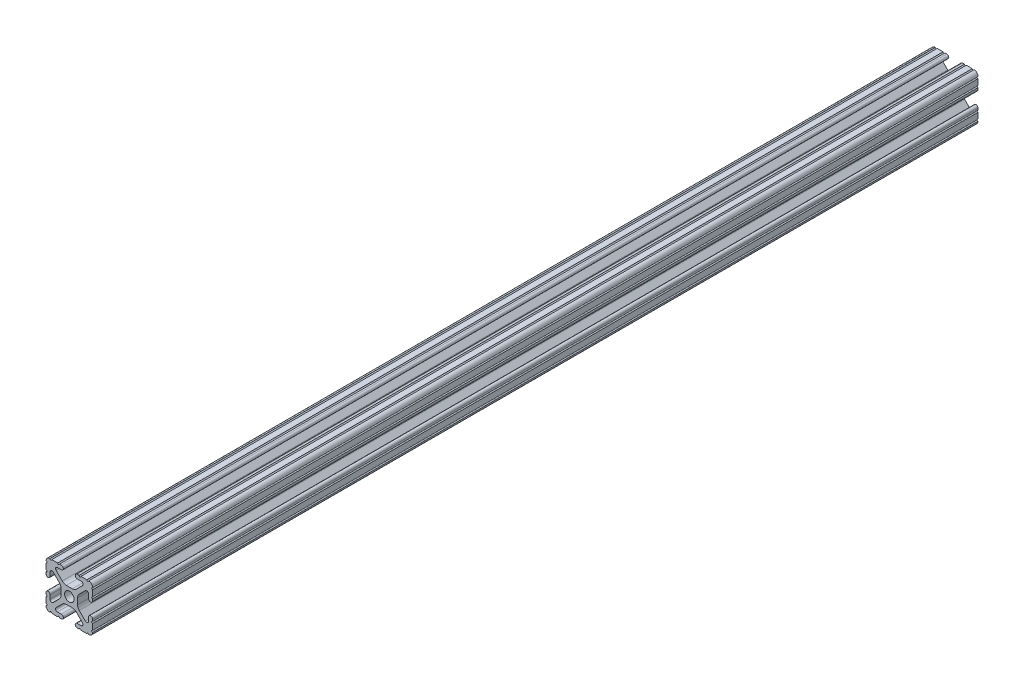
SolidWorks part; units mm, degrees
material "6061 Alloy"
ref_plane "Front Plane" through (0, 0, 0) normal (0, 0, 1) x (1, 0, 0)
ref_plane "Top Plane" through (0, 0, 0) normal (0, 1, 0) x (1, 0, 0)
ref_plane "Right Plane" through (0, 0, 0) normal (1, 0, 0) x (0, 0, -1)
ref_plane "Plane1" through (0, 0, -25.4) normal (0, 0, -1) x (-1, 0, 0)
sketch "Sketch1" plane through (0, 0, -25.4) normal (0, 0, -1) x (-1, 0, 0)
  line L0 (12.7, -9.5504) -> (12.7, -6.3331)
  line L1 (12.7, -5.3171) -> (12.7, -4.3434)
  line L2 (10.4902, -4.3434) -> (10.4902, -6.4748)
  line L3 (8.7558, -7.1932) -> (5.4257, -3.8632)
  line L4 (4.4958, -1.6181) -> (4.4958, 1.6181)
  line L5 (5.4257, 3.8632) -> (8.7558, 7.1932)
  line L6 (10.4902, 6.4748) -> (10.4902, 4.3434)
  line L7 (12.7, 4.3434) -> (12.7, 5.3171)
  line L8 (12.7, 6.3331) -> (12.7, 9.5504)
  line L9 (9.5504, 12.7) -> (6.3331, 12.7)
  line L10 (5.3171, 12.7) -> (4.3434, 12.7)
  line L11 (4.3434, 10.4902) -> (6.4748, 10.4902)
  line L12 (7.1932, 8.7558) -> (3.8632, 5.4257)
  line L13 (1.6181, 4.4958) -> (-1.6181, 4.4958)
  line L14 (-3.8632, 5.4257) -> (-7.1932, 8.7558)
  line L15 (-6.4748, 10.4902) -> (-4.3434, 10.4902)
  line L16 (-4.3434, 12.7) -> (-5.3171, 12.7)
  line L17 (-6.3331, 12.7) -> (-9.5504, 12.7)
  line L18 (-12.7, 9.5504) -> (-12.7, 6.3331)
  line L19 (-12.7, 5.3171) -> (-12.7, 4.3434)
  line L20 (-10.4902, 4.3434) -> (-10.4902, 6.4748)
  line L21 (-8.7558, 7.1932) -> (-5.4257, 3.8632)
  line L22 (-4.4958, 1.6181) -> (-4.4958, -1.6181)
  line L23 (-5.4257, -3.8632) -> (-8.7558, -7.1932)
  line L24 (-10.4902, -6.4748) -> (-10.4902, -4.3434)
  line L25 (-12.7, -4.3434) -> (-12.7, -5.3171)
  line L26 (-12.7, -6.3331) -> (-12.7, -9.5504)
  line L27 (-9.5504, -12.7) -> (-6.3331, -12.7)
  line L28 (-5.3171, -12.7) -> (-4.3434, -12.7)
  line L29 (-4.3434, -10.4902) -> (-6.4748, -10.4902)
  line L30 (-7.1932, -8.7558) -> (-3.8632, -5.4257)
  line L31 (-1.6181, -4.4958) -> (1.6181, -4.4958)
  line L32 (3.8632, -5.4257) -> (7.1932, -8.7558)
  line L33 (6.4748, -10.4902) -> (4.3434, -10.4902)
  line L34 (4.3434, -12.7) -> (5.3171, -12.7)
  line L35 (6.3331, -12.7) -> (9.5504, -12.7)
  arc A0 (12.6998, -10.5664) -> (12.7, -9.5504) centre (12.7, -10.0584) cw
  arc A1 (12.7, -6.3331) -> (12.7, -5.3171) centre (12.7, -5.8251) cw
  arc A2 (12.7, -4.3434) -> (10.4902, -4.3434) centre (11.5951, -4.3434) ccw
  arc A3 (10.4902, -6.4748) -> (8.7558, -7.1932) centre (9.4742, -6.4748) cw
  arc A4 (5.4257, -3.8632) -> (4.4958, -1.6181) centre (7.6708, -1.6181) cw
  arc A5 (4.4958, 1.6181) -> (5.4257, 3.8632) centre (7.6708, 1.6181) cw
  arc A6 (8.7558, 7.1932) -> (10.4902, 6.4748) centre (9.4742, 6.4748) cw
  arc A7 (10.4902, 4.3434) -> (12.7, 4.3434) centre (11.5951, 4.3434) ccw
  arc A8 (12.7, 5.3171) -> (12.7, 6.3331) centre (12.7, 5.8251) cw
  arc A9 (12.7, 9.5504) -> (12.6998, 10.5664) centre (12.7, 10.0584) cw
  arc A10 (12.6998, 10.5664) -> (10.5664, 12.6998) centre (10.5918, 10.5918) ccw
  arc A11 (10.5664, 12.6998) -> (9.5504, 12.7) centre (10.0584, 12.7) cw
  arc A12 (6.3331, 12.7) -> (5.3171, 12.7) centre (5.8251, 12.7) cw
  arc A13 (4.3434, 12.7) -> (4.3434, 10.4902) centre (4.3434, 11.5951) ccw
  arc A14 (6.4748, 10.4902) -> (7.1932, 8.7558) centre (6.4748, 9.4742) cw
  arc A15 (3.8632, 5.4257) -> (1.6181, 4.4958) centre (1.6181, 7.6708) cw
  arc A16 (-1.6181, 4.4958) -> (-3.8632, 5.4257) centre (-1.6181, 7.6708) cw
  arc A17 (-7.1932, 8.7558) -> (-6.4748, 10.4902) centre (-6.4748, 9.4742) cw
  arc A18 (-4.3434, 10.4902) -> (-4.3434, 12.7) centre (-4.3434, 11.5951) ccw
  arc A19 (-5.3171, 12.7) -> (-6.3331, 12.7) centre (-5.8251, 12.7) cw
  arc A20 (-9.5504, 12.7) -> (-10.5664, 12.6998) centre (-10.0584, 12.7) cw
  arc A21 (-10.5664, 12.6998) -> (-12.6998, 10.5664) centre (-10.5918, 10.5918) ccw
  arc A22 (-12.6998, 10.5664) -> (-12.7, 9.5504) centre (-12.7, 10.0584) cw
  arc A23 (-12.7, 6.3331) -> (-12.7, 5.3171) centre (-12.7, 5.8251) cw
  arc A24 (-12.7, 4.3434) -> (-10.4902, 4.3434) centre (-11.5951, 4.3434) ccw
  arc A25 (-10.4902, 6.4748) -> (-8.7558, 7.1932) centre (-9.4742, 6.4748) cw
  arc A26 (-5.4257, 3.8632) -> (-4.4958, 1.6181) centre (-7.6708, 1.6181) cw
  arc A27 (-4.4958, -1.6181) -> (-5.4257, -3.8632) centre (-7.6708, -1.6181) cw
  arc A28 (-8.7558, -7.1932) -> (-10.4902, -6.4748) centre (-9.4742, -6.4748) cw
  arc A29 (-10.4902, -4.3434) -> (-12.7, -4.3434) centre (-11.5951, -4.3434) ccw
  arc A30 (-12.7, -5.3171) -> (-12.7, -6.3331) centre (-12.7, -5.8251) cw
  arc A31 (-12.7, -9.5504) -> (-12.6998, -10.5664) centre (-12.7, -10.0584) cw
  arc A32 (-12.6998, -10.5664) -> (-10.5664, -12.6998) centre (-10.5918, -10.5918) ccw
  arc A33 (-10.5664, -12.6998) -> (-9.5504, -12.7) centre (-10.0584, -12.7) cw
  arc A34 (-6.3331, -12.7) -> (-5.3171, -12.7) centre (-5.8251, -12.7) cw
  arc A35 (-4.3434, -12.7) -> (-4.3434, -10.4902) centre (-4.3434, -11.5951) ccw
  arc A36 (-6.4748, -10.4902) -> (-7.1932, -8.7558) centre (-6.4748, -9.4742) cw
  arc A37 (-3.8632, -5.4257) -> (-1.6181, -4.4958) centre (-1.6181, -7.6708) cw
  arc A38 (1.6181, -4.4958) -> (3.8632, -5.4257) centre (1.6181, -7.6708) cw
  arc A39 (7.1932, -8.7558) -> (6.4748, -10.4902) centre (6.4748, -9.4742) cw
  arc A40 (4.3434, -10.4902) -> (4.3434, -12.7) centre (4.3434, -11.5951) ccw
  arc A41 (5.3171, -12.7) -> (6.3331, -12.7) centre (5.8251, -12.7) cw
  arc A42 (9.5504, -12.7) -> (10.5664, -12.6998) centre (10.0584, -12.7) cw
  arc A43 (10.5664, -12.6998) -> (12.6998, -10.5664) centre (10.5918, -10.5918) ccw
  circle A44 centre (0, 0) radius 2.6035
extrude "Boss-Extrude1" add sketch "Sketch1" against normal blind 482.6
